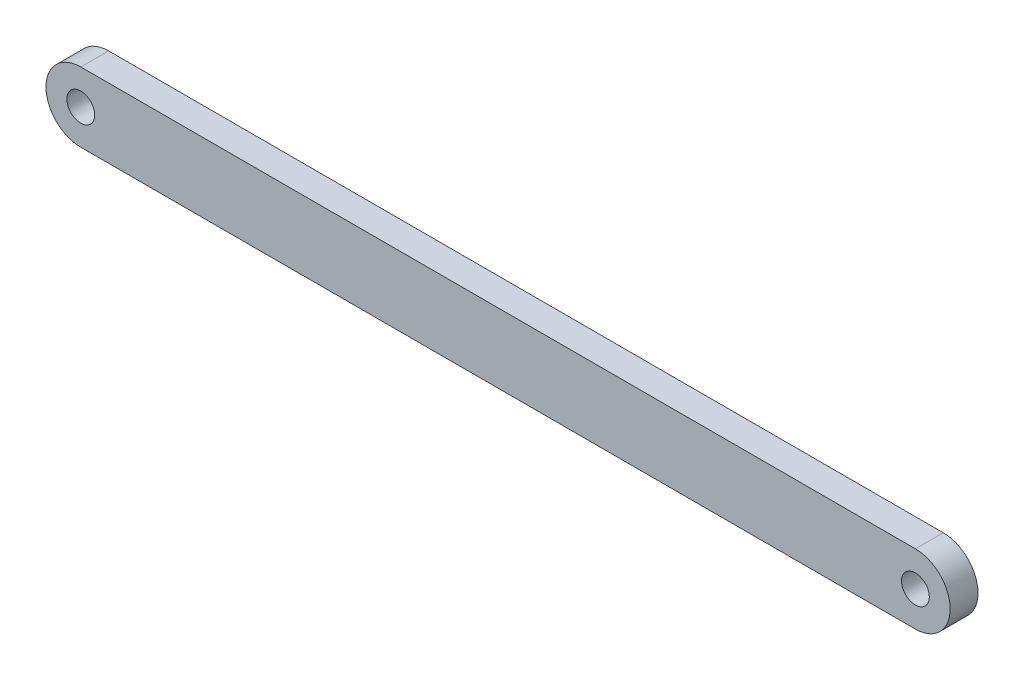
SolidWorks part; units mm, degrees
ref_plane "Front Plane" through (0, 0, 0) normal (0, 0, 1) x (1, 0, 0)
ref_plane "Top Plane" through (0, 0, 0) normal (0, 1, 0) x (1, 0, 0)
ref_plane "Right Plane" through (0, 0, 0) normal (1, 0, 0) x (0, 0, -1)
sketch "Sketch1" plane through (0, 0, 0) normal (0, 0, 1) x (1, 0, 0)
  line L0 (0, -5) -> (0, 5)
  line L1 (60, 5) -> (-60, 5)
  line L2 (60, 5) -> (60, -5)
  line L3 (60, -5) -> (-60, -5)
  line L4 (-60, 5) -> (-60, -5)
  line L5 (60, 5) -> (-60, -5) construction
  line L6 (60, -5) -> (-60, 5) construction
  circle A0 centre (-60, 0) radius 5
  circle A1 centre (-60, 0) radius 2
  circle A2 centre (60, 0) radius 5
  circle A3 centre (60, 0) radius 2
  point P0 (0, 0)
extrude "Boss-Extrude1" add sketch "Sketch1" along normal blind 4 contours A2 L1 A0 L3 | A1 L4 A0 | A1 L4 A0 | A3 L2 A2 | A3 L2 A2 | A0 L3 L0 L1
